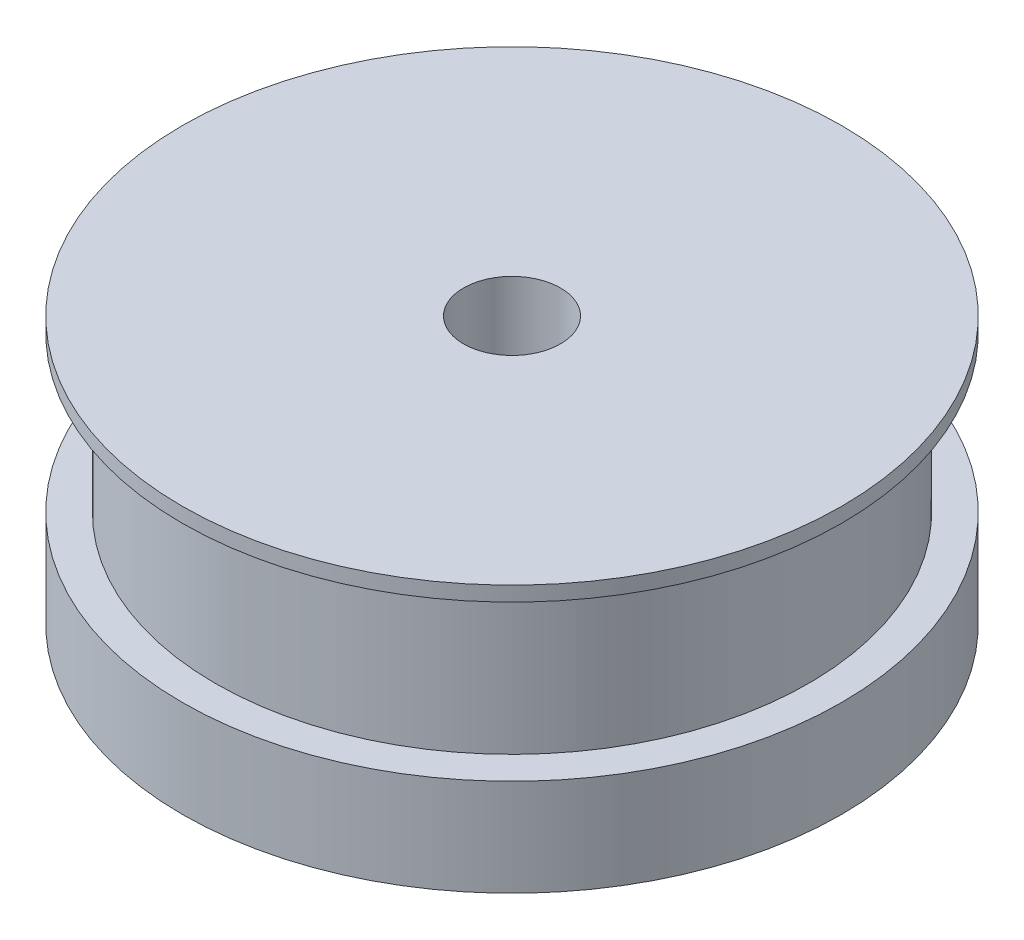
SolidWorks part; units mm, degrees
ref_plane "Front Plane" through (0, 0, 0) normal (0, 0, 1) x (1, 0, 0)
ref_plane "Top Plane" through (0, 0, 0) normal (0, 1, 0) x (1, 0, 0)
ref_plane "Right Plane" through (0, 0, 0) normal (1, 0, 0) x (0, 0, -1)
sketch "Sketch1" plane through (0, 0, 0) normal (0, 1, 0) x (1, 0, 0)
  circle A0 centre (0, 0) radius 21.59
  dimension "D1" = 43.18
extrude "Boss-Extrude1" add sketch "Sketch1" along normal blind 17.4752
sketch "Sketch2" plane through (0, 0, 0) normal (1, 0, 0) x (0, 0, -1)
  line L0 (0, 18.3093) -> (0, 0) construction
  line L1 (21.59, 0) -> (21.59, 17.4752) construction
  line L2 (21.59, 16.51) -> (19.431, 16.51)
  line L3 (21.59, 16.51) -> (21.59, 6.35)
  line L4 (21.59, 6.35) -> (19.431, 6.35)
  line L5 (19.431, 16.51) -> (19.431, 6.35)
  line L6 (-21.59, 0) -> (21.59, 0) construction
  point P9 (20.5105, 6.35)
  dimension "D1" = 10.16
  dimension "D2" = 6.35
  dimension "D3" = 38.862
revolve "Cut-Revolve1" cut sketch "Sketch2" angle 360 about L0
sketch "Sketch3" plane through (0, 17.4752, 0) normal (0, 1, 0) x (1, 0, 0)
  circle A0 centre (0, 0) radius 3.175
  dimension "D1" = 6.35
extrude "Cut-Extrude1" cut sketch "Sketch3" against normal blind 17.4752
